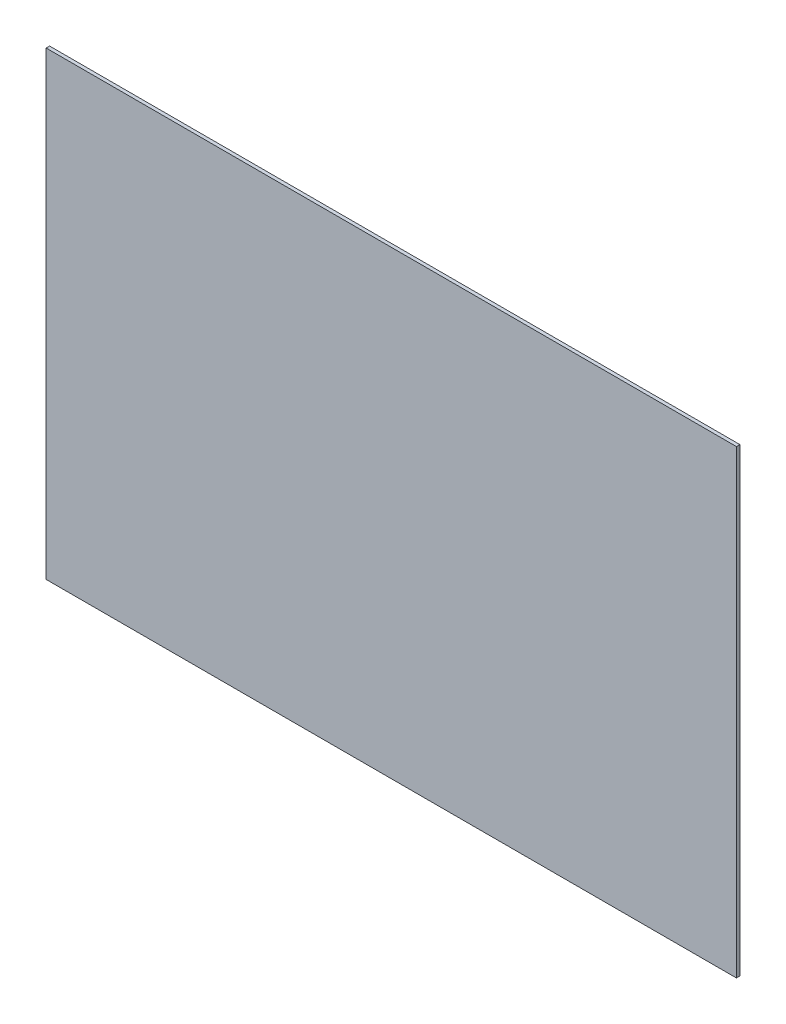
SolidWorks part; units mm, degrees
ref_plane "Płaszczyzna przednia" through (0, 0, 0) normal (0, 0, 1) x (1, 0, 0)
ref_plane "Płaszczyzna górna" through (0, 0, 0) normal (0, 1, 0) x (1, 0, 0)
ref_plane "Płaszczyzna prawa" through (0, 0, 0) normal (1, 0, 0) x (0, 0, -1)
sketch "Szkic1" plane through (0, 0, 0) normal (0, 0, 1) x (1, 0, 0)
  line L1 (-479.2211, 123.2394) -> (120.7789, 123.2394)
  line L2 (-479.2211, 123.2394) -> (-479.2211, -276.7606)
  line L3 (-479.2211, -276.7606) -> (120.7789, -276.7606)
  line L4 (120.7789, 123.2394) -> (120.7789, -276.7606)
  dimension "D1" = 600
  dimension "D2" = 400
extrude "Dodanie-wyciągnięcie1" add sketch "Szkic1" along normal blind 3
